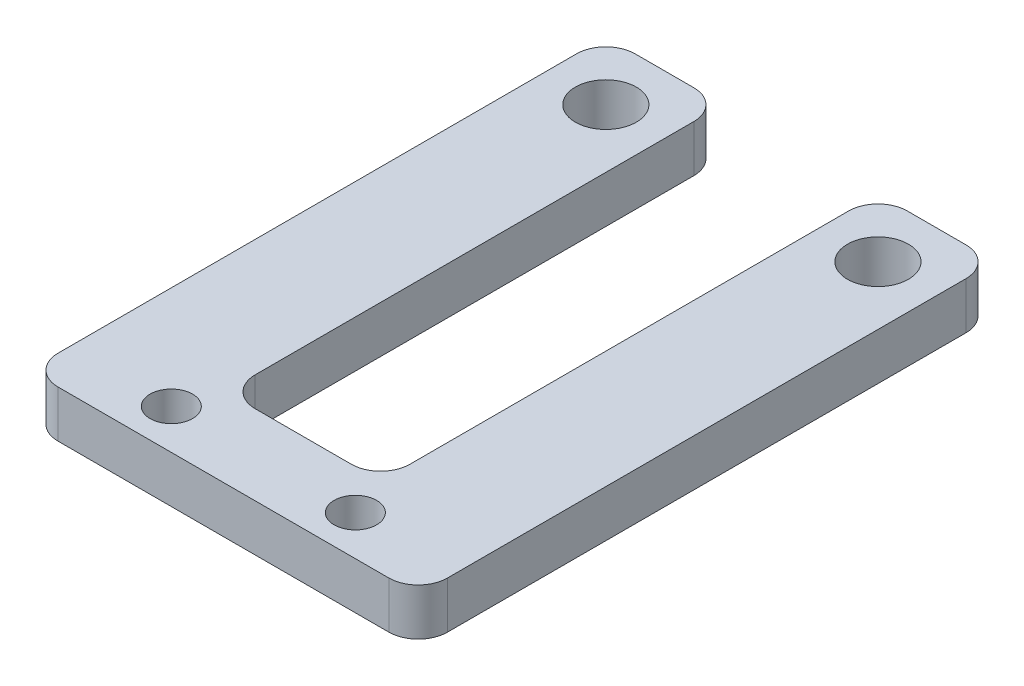
SolidWorks part; units mm, degrees
ref_plane "Front Plane" through (0, 0, 0) normal (0, 0, 1) x (1, 0, 0)
ref_plane "Top Plane" through (0, 0, 0) normal (0, 1, 0) x (1, 0, 0)
ref_plane "Right Plane" through (0, 0, 0) normal (1, 0, 0) x (0, 0, -1)
sketch "Sketch1" plane through (0, 0, 0) normal (0, 1, 0) x (1, 0, 0)
  line L0 (0, -1.5875) -> (0, -29.6545)
  line L1 (1.5875, -31.242) -> (19.4945, -31.242)
  line L3 (13.1445, -26.924) -> (7.9375, -26.924)
  line L4 (6.35, -25.3365) -> (6.35, -1.5875)
  line L5 (4.7625, 0) -> (1.5875, 0)
  line L6 (3.175, 0) -> (3.175, -3.175) construction
  line L7 (10.541, -26.924) -> (10.541, -3.8379) construction
  line L8 (7.7718, -26.924) -> (7.7718, -31.242) construction
  line L9 (17.907, 0) -> (17.907, -3.175) construction
  line L10 (16.3195, 0) -> (19.4945, 0)
  line L11 (14.732, -25.3365) -> (14.732, -1.5875)
  line L12 (21.082, -1.5875) -> (21.082, -29.6545)
  circle A0 centre (3.175, -3.175) radius 1.65
  circle A1 centre (5.5593, -29.083) radius 1.15
  circle A2 centre (15.5227, -29.083) radius 1.15
  circle A3 centre (17.907, -3.175) radius 1.65
  arc A4 (0, -1.5875) -> (1.5875, 0) centre (1.5875, -1.5875) cw
  arc A5 (6.35, -1.5875) -> (4.7625, 0) centre (4.7625, -1.5875) ccw
  arc A6 (16.3195, 0) -> (14.732, -1.5875) centre (16.3195, -1.5875) ccw
  arc A7 (19.4945, 0) -> (21.082, -1.5875) centre (19.4945, -1.5875) cw
  arc A8 (21.082, -29.6545) -> (19.4945, -31.242) centre (19.4945, -29.6545) cw
  arc A9 (14.732, -25.3365) -> (13.1445, -26.924) centre (13.1445, -25.3365) cw
  arc A10 (7.9375, -26.924) -> (6.35, -25.3365) centre (7.9375, -25.3365) cw
  arc A11 (0, -29.6545) -> (1.5875, -31.242) centre (1.5875, -29.6545) ccw
  point P16 (7.7718, -29.083)
  point P28 (0, 0)
  point P31 (6.35, 0)
  point P34 (14.732, 0)
  point P37 (21.082, 0)
  point P40 (21.082, -31.242)
  point P43 (14.732, -26.924)
  point P46 (6.35, -26.924)
  point P49 (0, -31.242)
  dimension "D1" = 3.3
  dimension "D5" = 4.9817
  dimension "D8" = 2.3
  dimension "D9" = 1.5875
  dimension "D2" = 3.175
  dimension "D3" = 6.35
  dimension "D4" = 4.318
  dimension "D6" = 14.732
  dimension "D7" = 25.908
extrude "Boss-Extrude1" add sketch "Sketch1" along normal blind 2.54
